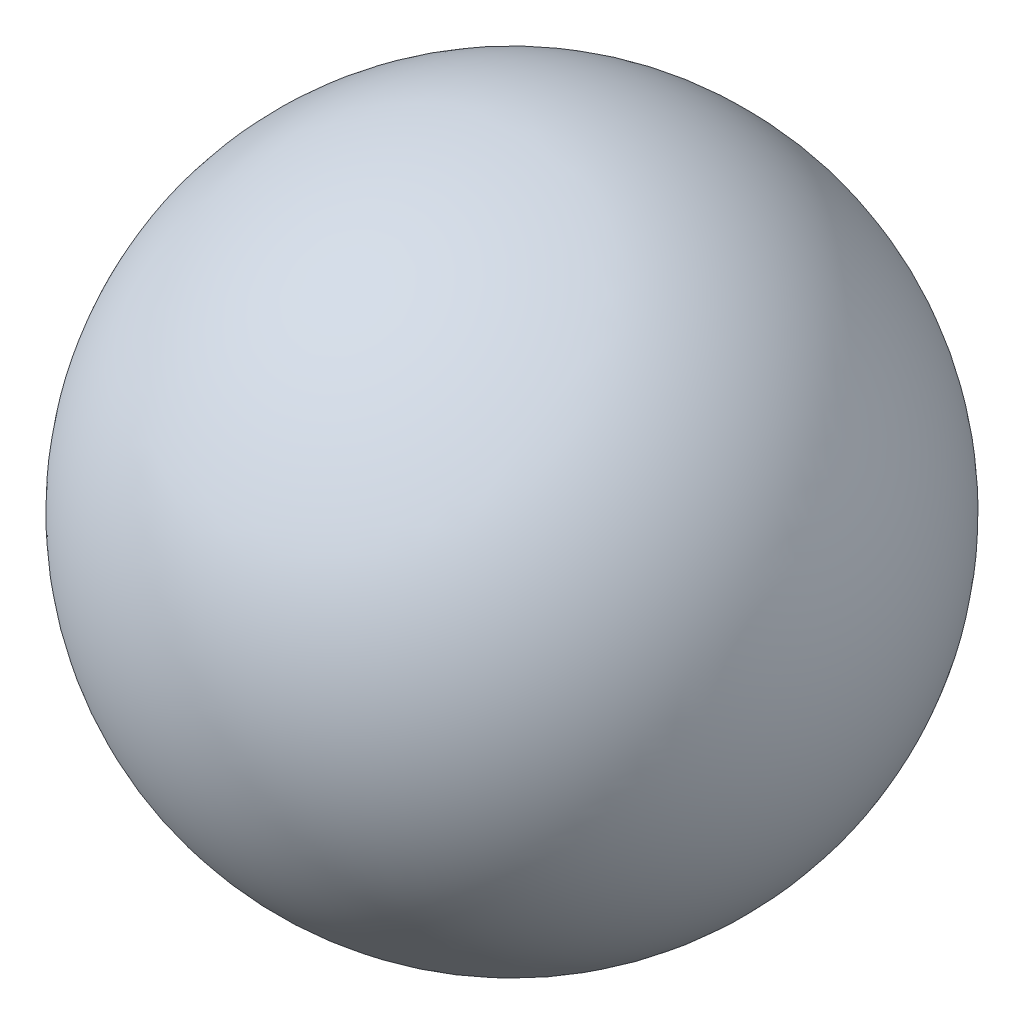
SolidWorks part; units mm, degrees
ref_plane "Piano frontale" through (0, 0, 0) normal (0, 0, 1) x (1, 0, 0)
ref_plane "Piano superiore" through (0, 0, 0) normal (0, 1, 0) x (1, 0, 0)
ref_plane "Piano destro" through (0, 0, 0) normal (1, 0, 0) x (0, 0, -1)
ref_plane "Piano1" through (0, 0, 0) normal (0, 0, 1) x (1, 0, 0)
sketch "Schizzo1" plane through (0, 0, 0) normal (0, 0, 1) x (1, 0, 0)
  line L0 (10.072, 53.75) -> (2.928, 53.75)
  line L1 (10.072, 53.75) -> (2.928, 53.75) construction
  arc A0 (2.928, 53.75) -> (10.072, 53.75) centre (6.5, 53.75) cw
revolve "Rivoluzione1" add sketch "Schizzo1" angle 360 about L1
